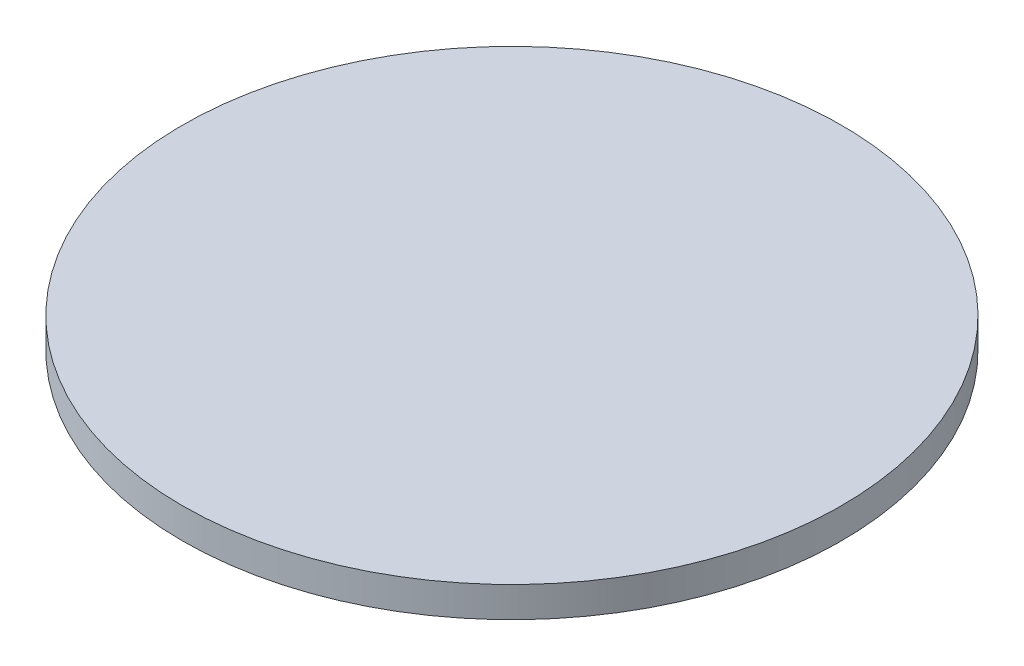
SolidWorks part; units mm, degrees
ref_plane "Ebene vorne" through (0, 0, 0) normal (0, 0, 1) x (1, 0, 0)
ref_plane "Ebene oben" through (0, 0, 0) normal (0, 1, 0) x (1, 0, 0)
ref_plane "Ebene rechts" through (0, 0, 0) normal (1, 0, 0) x (0, 0, -1)
sketch "Sketch1" plane through (0, 0, 0) normal (0, 1, 0) x (1, 0, 0)
  circle A0 centre (0, 0) radius 2.7
  dimension "D1" = 5.4
extrude "Boss-Extrude1" add sketch "Sketch1" along normal blind 10 draft 55 draft outward yes
sketch "Sketch2" plane through (0, 10, 0) normal (0, 1, 0) x (1, 0, 0)
  circle A0 centre (0, 0) radius 15
  circle A1 centre (0, 0) radius 16.9815
  circle A2 centre (0, 0) radius 16.9815 construction
  dimension "D1" = 30
extrude "Cut-Extrude1" cut sketch "Sketch2" against normal up to next
